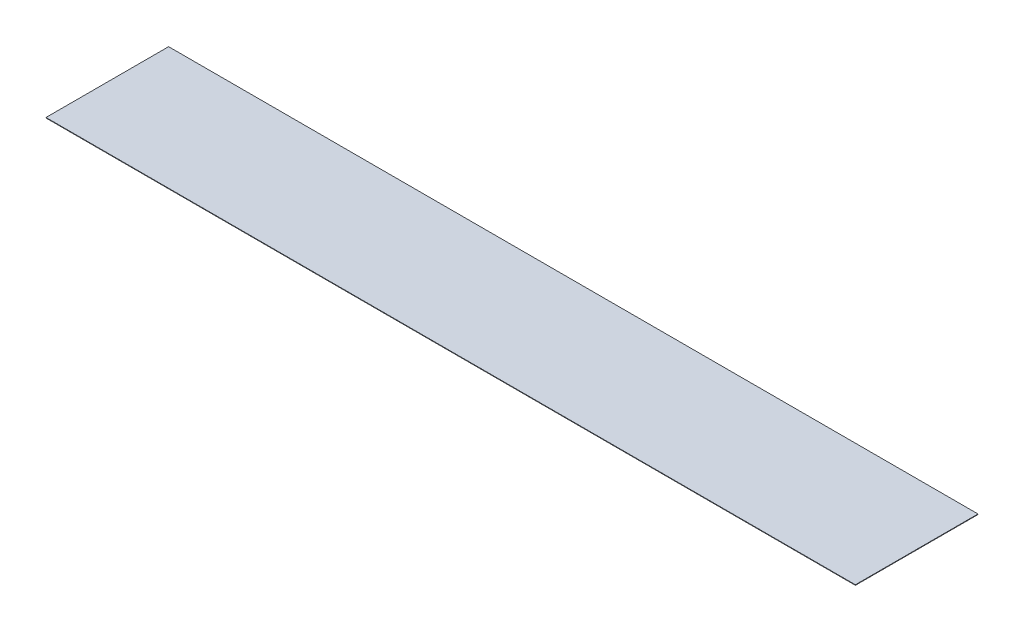
SolidWorks part; units mm, degrees
ref_plane "Front Plane" through (0, 0, 0) normal (0, 0, 1) x (1, 0, 0)
ref_plane "Top Plane" through (0, 0, 0) normal (0, 1, 0) x (1, 0, 0)
ref_plane "Right Plane" through (0, 0, 0) normal (1, 0, 0) x (0, 0, -1)
sketch "Sketch1" plane through (0, 0, 0) normal (0, 1, 0) x (1, 0, 0)
  line L1 (-7967.5, 1207) -> (7967.5, 1207)
  line L2 (-7967.5, 1207) -> (-7967.5, -1207)
  line L3 (-7967.5, -1207) -> (7967.5, -1207)
  line L4 (7967.5, 1207) -> (7967.5, -1207)
  line L5 (-7967.5, 1207) -> (7967.5, -1207) construction
  line L6 (-7967.5, -1207) -> (7967.5, 1207) construction
  point P0 (0, 0)
  dimension "D1" = 15935
  dimension "2000" = 2414
extrude "Boss-Extrude1" add sketch "Sketch1" along normal blind 10
